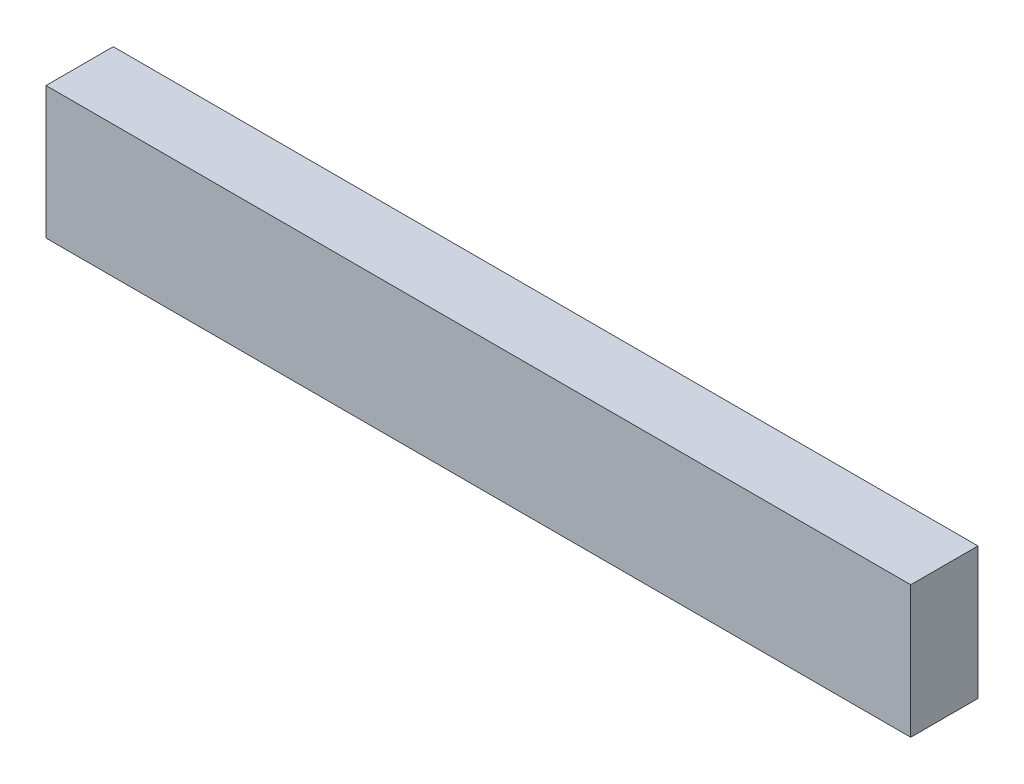
SolidWorks part; units mm, degrees
ref_plane "前视基准面" through (0, 0, 0) normal (0, 0, 1) x (1, 0, 0)
ref_plane "上视基准面" through (0, 0, 0) normal (0, 1, 0) x (1, 0, 0)
ref_plane "右视基准面" through (0, 0, 0) normal (1, 0, 0) x (0, 0, -1)
other "Configuration Table"
sketch "草图1" plane through (0, 0, 0) normal (0, 0, 1) x (1, 0, 0)
  line L1 (-180, -27.5) -> (180, -27.5)
  line L2 (-180, -27.5) -> (-180, 27.5)
  line L3 (-180, 27.5) -> (180, 27.5)
  line L4 (180, -27.5) -> (180, 27.5)
  line L5 (-180, -27.5) -> (180, 27.5) construction
  line L6 (-180, 27.5) -> (180, -27.5) construction
  point P0 (0, 0)
extrude "凸台-拉伸1" add sketch "草图1" along normal blind 28
